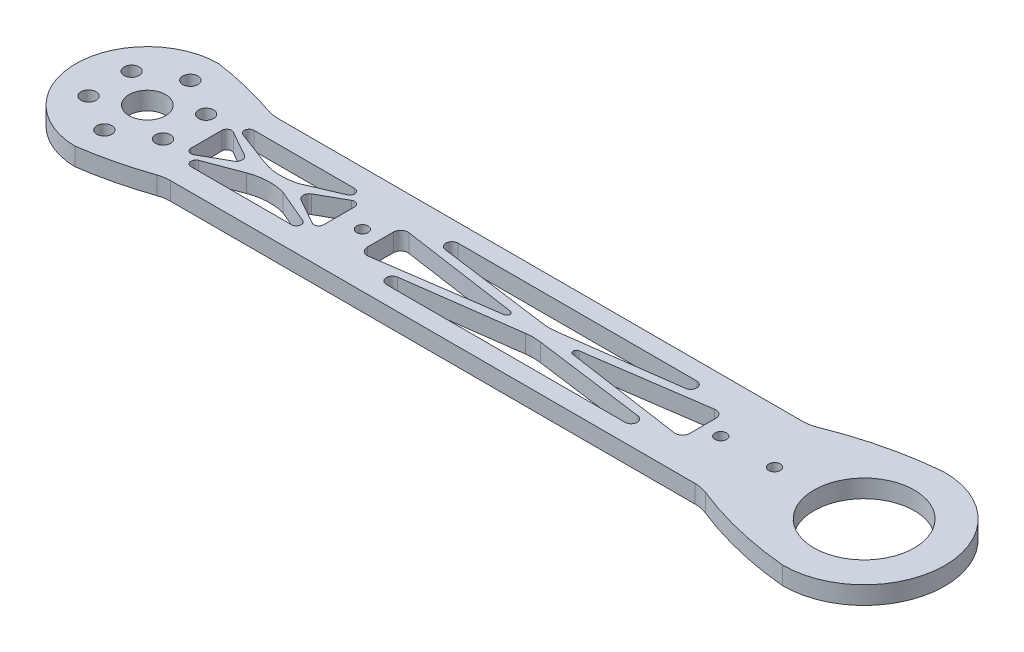
SolidWorks part; units mm, degrees
material "Thornel Mat VMA"
ref_plane "前视基准面" through (0, 0, 0) normal (0, 0, 1) x (1, 0, 0)
ref_plane "上视基准面" through (0, 0, 0) normal (0, 1, 0) x (1, 0, 0)
ref_plane "右视基准面" through (0, 0, 0) normal (1, 0, 0) x (0, 0, -1)
sketch "草图1" plane through (0, 0, 0) normal (0, 1, 0) x (1, 0, 0)
  line L0 (-0.25, 19.9984) -> (199.7188, 22.4982)
  line L5 (300, 0) -> (-49700, 0) construction
  line L6 (-0.25, -19.9984) -> (199.7188, -22.4982)
  arc A0 (-0.25, 19.9984) -> (-0.25, -19.9984) centre (0, 0) ccw
  arc A1 (199.7188, -22.4982) -> (199.7188, 22.4982) centre (200, 0) ccw
  point P0 (0, 0)
  dimension "D1" = 40
  dimension "D2" = 45
  dimension "D3" = 200
extrude "凸台-拉伸1" add sketch "草图1" along normal blind 5
sketch "草图2" plane through (0, 5, 0) normal (0, 1, 0) x (1, 0, 0)
  circle A0 centre (0, 0) radius 5.1
  dimension "D1" = 10.2
extrude "切除-拉伸1" cut sketch "草图2" against normal blind 10
sketch "草图3" plane through (0, 5, 0) normal (0, 1, 0) x (1, 0, 0)
  circle A0 centre (200, 0) radius 14
  dimension "D1" = 28
extrude "切除-拉伸2" cut sketch "草图3" against normal blind 10
sketch "草图4" plane through (0, 5, 0) normal (0, 1, 0) x (1, 0, 0)
  line L0 (0, 0) -> (0, 50000) construction
  circle A0 centre (0, 0) radius 12 construction
  circle A1 centre (0, 12) radius 2.1
  circle A2 centre (10.3923, 6) radius 2.1
  circle A3 centre (10.3923, -6) radius 2.1
  circle A4 centre (0, -12) radius 2.1
  circle A5 centre (-10.3923, -6) radius 2.1
  circle A6 centre (-10.3923, 6) radius 2.1
  point P15 (0, 0)
  point P27 (0, 0)
  dimension "D1" = 24
  dimension "D2" = 4.2
  dimension "D3" = 6
extrude "切除-拉伸3" cut sketch "草图4" against normal blind 10
sketch "草图6" plane through (0, 5, 0) normal (0, 1, 0) x (1, 0, 0)
  line L0 (60, 15) -> (160.4981, 9.9876)
  line L1 (60, -15) -> (160.4981, -9.9876)
  arc A0 (60, 15) -> (60, -15) centre (60, 0) ccw
  arc A1 (160.4981, -9.9876) -> (160.4981, 9.9876) centre (160, 0) ccw
  dimension "D3" = 30
  dimension "D4" = 20
  dimension "D1" = 100
  dimension "D2" = 60
sketch "草图8" plane through (0, 5, 0) normal (0, 1, 0) x (1, 0, 0)
  line L0 (-0.25, 11.9978) -> (199.7188, 14.4976) construction
  line L1 (199.7188, 22.4982) -> (-0.25, 19.9984) construction
  line L2 (0, 0) -> (50000, 0) construction
  circle A0 centre (65, 12.8135) radius 1.6
  circle A2 centre (114.8261, 8.6468) radius 1.6
  circle A3 centre (164.6522, 4.4802) radius 1.6
  circle A6 centre (164.6522, -4.4802) radius 1.6
  circle A7 centre (114.8261, -8.6468) radius 1.6
  circle A8 centre (65, -12.8135) radius 1.6
  dimension "D2" = 3.2
  dimension "D1" = 8
  dimension "D3" = 65
  dimension "D4" = 3
  dimension "D5" = 50
sketch "草图10" plane through (0, 5, 0) normal (0, 1, 0) x (1, 0, 0)
  line L1 (19.75, 15) -> (169.7188, 15)
  line L2 (19.75, 15) -> (19.75, -15) construction
  line L3 (19.75, -15) -> (169.7188, -15)
  line L4 (169.7188, 15) -> (169.7188, -15) construction
  line L5 (19.75, 15) -> (169.7188, -15) construction
  line L6 (19.75, -15) -> (169.7188, 15) construction
  line L8 (-0.25, 19.9984) -> (199.7188, 22.4982)
  line L9 (-0.25, -19.9984) -> (199.7188, -22.4982)
  arc A0 (-0.25, 19.9984) -> (19.75, 15) centre (-14.3673, -79.0001) cw
  arc A1 (-0.25, -19.9984) -> (19.75, -15) centre (-14.3673, 79.0001) ccw
  arc A2 (199.7188, 22.4982) -> (169.7188, 15) centre (208.6754, -77.0998) ccw
  arc A3 (199.7188, -22.4982) -> (169.7188, -15) centre (208.6754, 77.0998) cw
  point P0 (94.7344, 0)
  dimension "D4" = 100
  dimension "D5" = 100
  dimension "D6" = 100
  dimension "D7" = 100
  dimension "D1" = 30
  dimension "D2" = 20
  dimension "D3" = 30
extrude "切除-拉伸4" cut sketch "草图10" against normal through all
fillet "圆角1" radius 10 4 edges at (169.7188, 2.5, -15) (169.7188, 2.5, 15) (19.75, 2.5, 15) (19.75, 2.5, -15)
sketch "草图12" plane through (0, 5, 0) normal (0, 1, 0) x (1, 0, 0)
  line L0 (65, -10) -> (155, -10) construction
  line L1 (65, -10) -> (65, 10) construction
  line L2 (65, 10) -> (155, 10) construction
  line L3 (155, -10) -> (155, 10) construction
  line L4 (106.3737, 0) -> (65, -6) construction
  line L5 (106.3737, 0) -> (65, 6) construction
  line L6 (65, 0) -> (155, 0) construction
  line L7 (110, 10) -> (110, -10) construction
  line L8 (42.4873, 10) -> (177.5127, 10) construction
  line L9 (51.6211, 10) -> (110, 2.1073) construction
  line L10 (110, 2.1073) -> (166.9475, 10) construction
  line L11 (76.6901, 10) -> (143.3099, 10)
  line L12 (65, 3.6155) -> (65, -3.6155)
  line L13 (76.4641, 6.6413) -> (107.8961, 2.3918)
  line L14 (112.103, 2.3988) -> (143.5359, 6.6413)
  line L15 (67.3598, -5.6578) -> (100.4288, -0.8621)
  line L16 (67.3598, 5.6578) -> (100.4288, 0.8621)
  line L17 (155, 3.6155) -> (155, -3.6155)
  line L18 (152.6402, -5.6578) -> (119.5712, -0.8621)
  line L19 (152.6402, 5.6578) -> (119.5712, 0.8621)
  line L20 (76.4641, -6.6413) -> (107.8961, -2.3918)
  line L21 (76.6901, -10) -> (143.3099, -10)
  line L22 (112.103, -2.3988) -> (143.5359, -6.6413)
  line L23 (167.741, -15) -> (21.4655, -15) construction
  circle A0 centre (200, 0) radius 14 construction
  circle A1 centre (160, 0) radius 1.6
  circle A2 centre (60, 0) radius 1.6
  arc A3 (65, 3.6155) -> (67.3598, 5.6578) centre (67.0636, 3.6155) cw
  arc A4 (100.4288, 0.8621) -> (100.4288, -0.8621) centre (100.3037, 0) cw
  arc A5 (65, -3.6155) -> (67.3598, -5.6578) centre (67.0636, -3.6155) ccw
  arc A6 (76.6901, 10) -> (76.4641, 6.6413) centre (76.6901, 8.313) ccw
  arc A7 (107.8961, 2.3918) -> (112.103, 2.3988) centre (109.9739, 17.7606) ccw
  arc A8 (143.3099, 10) -> (143.5359, 6.6413) centre (143.3099, 8.313) cw
  arc A9 (155, 3.6155) -> (152.6402, 5.6578) centre (152.9364, 3.6155) ccw
  arc A10 (155, -3.6155) -> (152.6402, -5.6578) centre (152.9364, -3.6155) cw
  arc A11 (119.5712, 0.8621) -> (119.5712, -0.8621) centre (119.6963, 0) ccw
  arc A12 (107.8961, -2.3918) -> (112.103, -2.3988) centre (109.9739, -17.7606) cw
  arc A13 (76.6901, -10) -> (76.4641, -6.6413) centre (76.6901, -8.313) cw
  arc A14 (143.3099, -10) -> (143.5359, -6.6413) centre (143.3099, -8.313) ccw
  circle A15 centre (175, 0) radius 1.6
  point P0 (110, 0)
  point P16 (110, 0)
  point P19 (110, 0)
  point P26 (110, 10)
  dimension "D3" = 3.2
  dimension "D4" = 3.2
  dimension "D9" = 3.2
  dimension "D1" = 90
  dimension "D2" = 40
  dimension "D5" = 100
  dimension "D6" = 5
  dimension "D7" = 5
  dimension "D8" = 12
  dimension "D10" = 15
extrude "切除-拉伸5" cut sketch "草图12" against normal through all
sketch "草图13" plane through (0, 5, 0) normal (0, 1, 0) x (1, 0, 0)
  line L0 (16.4904, -8.7851) -> (53.5096, -8.7851) construction
  line L7 (16.4904, -8.7851) -> (16.4904, 8.7851) construction
  line L8 (16.4904, 8.7851) -> (53.5096, 8.7851) construction
  line L9 (53.5096, -8.7851) -> (53.5096, 8.7851) construction
  line L10 (28.2215, 0) -> (16.4904, -6.6191) construction
  line L11 (28.2215, 0) -> (16.4904, 6.6191) construction
  line L12 (16.4904, 0) -> (53.5096, 0) construction
  line L13 (35, 8.7851) -> (35, -8.7851) construction
  line L14 (16.4904, 8.7851) -> (53.5096, 8.7851) construction
  line L15 (13.5821, 8.7851) -> (35, 0.7282) construction
  line L16 (35, 0.7282) -> (63.8301, 8.7851) construction
  line L17 (20.9708, 8.7851) -> (49.0292, 8.7851)
  line L18 (16.4904, 4.318) -> (16.4904, -4.318)
  line L19 (20.4977, 6.1836) -> (30.1822, 2.5405)
  line L20 (39.9574, 2.1136) -> (49.5023, 6.1836)
  line L21 (18.4945, -5.4883) -> (25.6422, -1.4553)
  line L22 (18.4945, 5.4883) -> (25.6422, 1.4553)
  line L23 (53.5096, 4.318) -> (53.5096, -4.318)
  line L24 (51.5055, -5.4883) -> (44.3578, -1.4553)
  line L25 (51.5055, 5.4883) -> (44.3578, 1.4553)
  line L26 (20.4977, -6.1836) -> (30.1822, -2.5405)
  line L27 (20.9708, -8.7851) -> (49.0292, -8.7851)
  line L28 (39.9574, -2.1136) -> (49.5023, -6.1836)
  arc A2 (16.4904, 4.318) -> (18.4945, 5.4883) centre (17.8342, 4.318) cw
  arc A3 (25.6422, 1.4553) -> (25.6422, -1.4553) centre (24.821, 0) cw
  arc A4 (16.4904, -4.318) -> (18.4945, -5.4883) centre (17.8342, -4.318) ccw
  arc A5 (20.9708, 8.7851) -> (20.4977, 6.1836) centre (20.9708, 7.4413) ccw
  arc A6 (30.1822, 2.5405) -> (39.9574, 2.1136) centre (35.7223, 17.2681) ccw
  arc A7 (49.0292, 8.7851) -> (49.5023, 6.1836) centre (49.0292, 7.4413) cw
  arc A8 (53.5096, 4.318) -> (51.5055, 5.4883) centre (52.1658, 4.318) ccw
  arc A9 (53.5096, -4.318) -> (51.5055, -5.4883) centre (52.1658, -4.318) cw
  arc A10 (44.3578, 1.4553) -> (44.3578, -1.4553) centre (45.179, 0) ccw
  arc A11 (30.1822, -2.5405) -> (39.9574, -2.1136) centre (35.7223, -17.2681) cw
  arc A12 (20.9708, -8.7851) -> (20.4977, -6.1836) centre (20.9708, -7.4413) cw
  arc A13 (49.0292, -8.7851) -> (49.5023, -6.1836) centre (49.0292, -7.4413) ccw
  circle A15 centre (0, 0) radius 5.1 construction
  point P0 (33.9417, 0)
  point P3 (35, 0)
  point P16 (35, 0)
  point P19 (35, 0)
  point P27 (35, 8.7851)
  dimension "D1" = 35
extrude "切除-拉伸6" cut sketch "草图13" against normal blind 10
